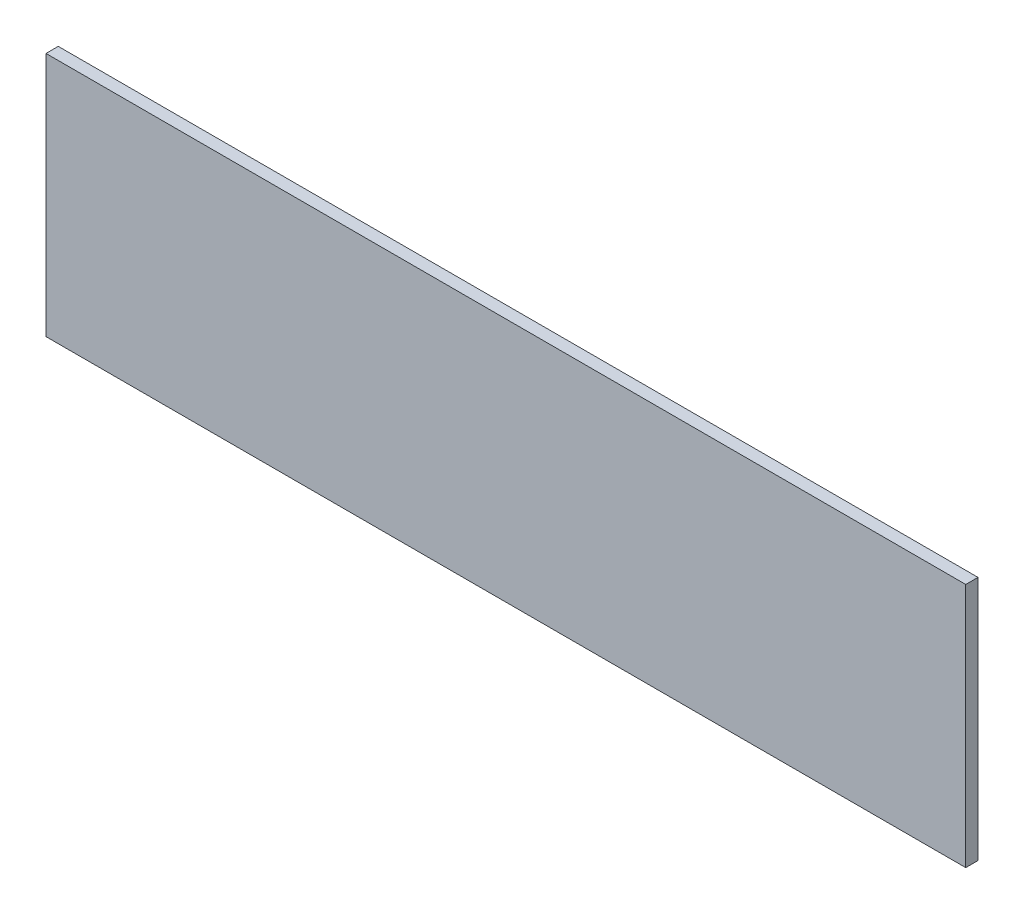
SolidWorks part; units mm, degrees
ref_plane "Alzado" through (0, 0, 0) normal (0, 0, 1) x (1, 0, 0)
ref_plane "Planta" through (0, 0, 0) normal (0, 1, 0) x (1, 0, 0)
ref_plane "Vista lateral" through (0, 0, 0) normal (1, 0, 0) x (0, 0, -1)
sketch "Croquis1" plane through (0, 0, 0) normal (0, 0, 1) x (1, 0, 0)
  line L1 (0, 0) -> (300, 0)
  line L2 (0, 0) -> (0, 80)
  line L3 (0, 80) -> (300, 80)
  line L4 (300, 0) -> (300, 80)
  dimension "D1" = 80
  dimension "D2" = 300
extrude "Saliente-Extruir1" add sketch "Croquis1" along normal blind 4
